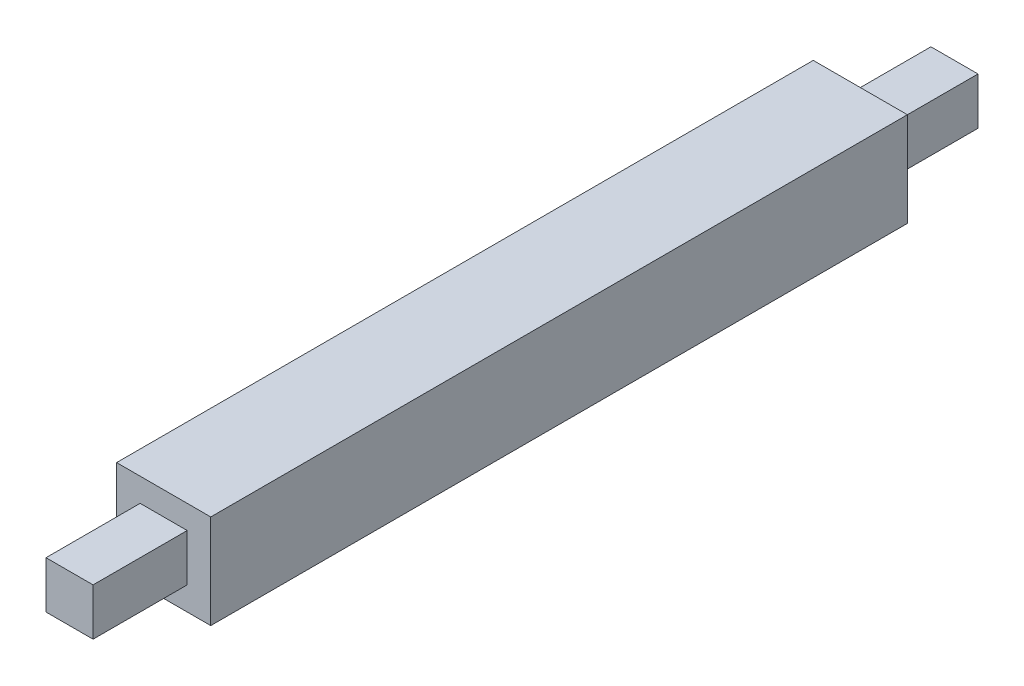
SolidWorks part; units mm, degrees
ref_plane "Front Plane" through (0, 0, 0) normal (0, 0, 1) x (1, 0, 0)
ref_plane "Top Plane" through (0, 0, 0) normal (0, 1, 0) x (1, 0, 0)
ref_plane "Right Plane" through (0, 0, 0) normal (1, 0, 0) x (0, 0, -1)
sketch "Sketch1" plane through (0, 0, 0) normal (0, 0, 1) x (1, 0, 0)
  line L1 (0, 0) -> (5, 0)
  line L2 (0, 0) -> (0, 5)
  line L3 (0, 5) -> (5, 5)
  line L4 (5, 0) -> (5, 5)
  dimension "D1" = 5
  dimension "D2" = 5
extrude "Boss-Extrude1" add sketch "Sketch1" along normal blind 37
sketch "Sketch2" plane through (0, 0, 37) normal (0, 0, 1) x (1, 0, 0)
  line L0 (0, 5) -> (0, 0) construction
  line L1 (1.25, 1.25) -> (3.75, 1.25)
  line L2 (1.25, 1.25) -> (1.25, 3.75)
  line L3 (1.25, 3.75) -> (3.75, 3.75)
  line L4 (3.75, 1.25) -> (3.75, 3.75)
  line L5 (5, 5) -> (0, 5) construction
  dimension "D1" = 2.5
  dimension "D2" = 2.5
  dimension "D3" = 1.25
  dimension "D4" = 1.25
extrude "Boss-Extrude2" add sketch "Sketch2" along normal blind 5
sketch "Sketch3" plane through (0, 0, 0) normal (0, 0, -1) x (-1, 0, 0)
  line L0 (-5, 0) -> (-5, 5) construction
  line L1 (-3.75, 1.25) -> (-1.25, 1.25)
  line L2 (-3.75, 1.25) -> (-3.75, 3.75)
  line L3 (-3.75, 3.75) -> (-1.25, 3.75)
  line L4 (-1.25, 1.25) -> (-1.25, 3.75)
  line L5 (-5, 5) -> (0, 5) construction
  dimension "D1" = 2.5
  dimension "D2" = 2.5
  dimension "D3" = 1.25
  dimension "D4" = 1.25
extrude "Boss-Extrude3" add sketch "Sketch3" along normal blind 5
